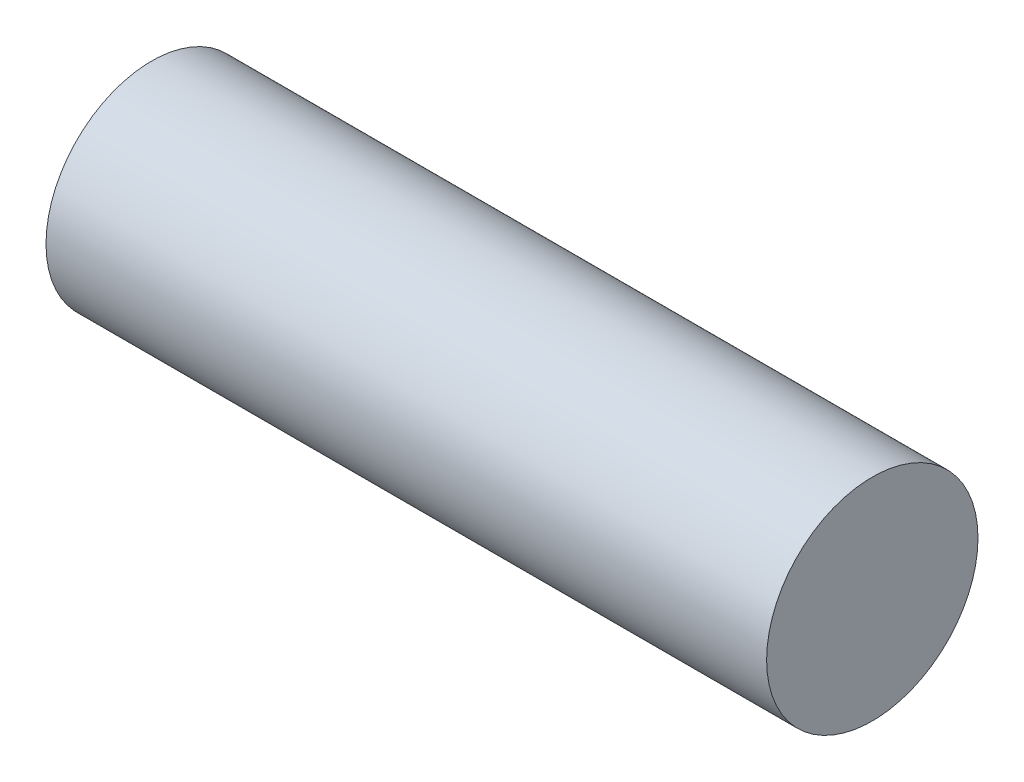
SolidWorks part; units mm, degrees
ref_plane "Front Plane" through (0, 0, 0) normal (0, 0, 1) x (1, 0, 0)
ref_plane "Top Plane" through (0, 0, 0) normal (0, 1, 0) x (1, 0, 0)
ref_plane "Right Plane" through (0, 0, 0) normal (1, 0, 0) x (0, 0, -1)
sketch "Sketch1" plane through (0, 0, 0) normal (1, 0, 0) x (0, 0, -1)
  circle A0 centre (0, 0) radius 4.4
  dimension "D1" = 8.8
extrude "Boss-Extrude1" add sketch "Sketch1" along normal blind 30 contours A0
